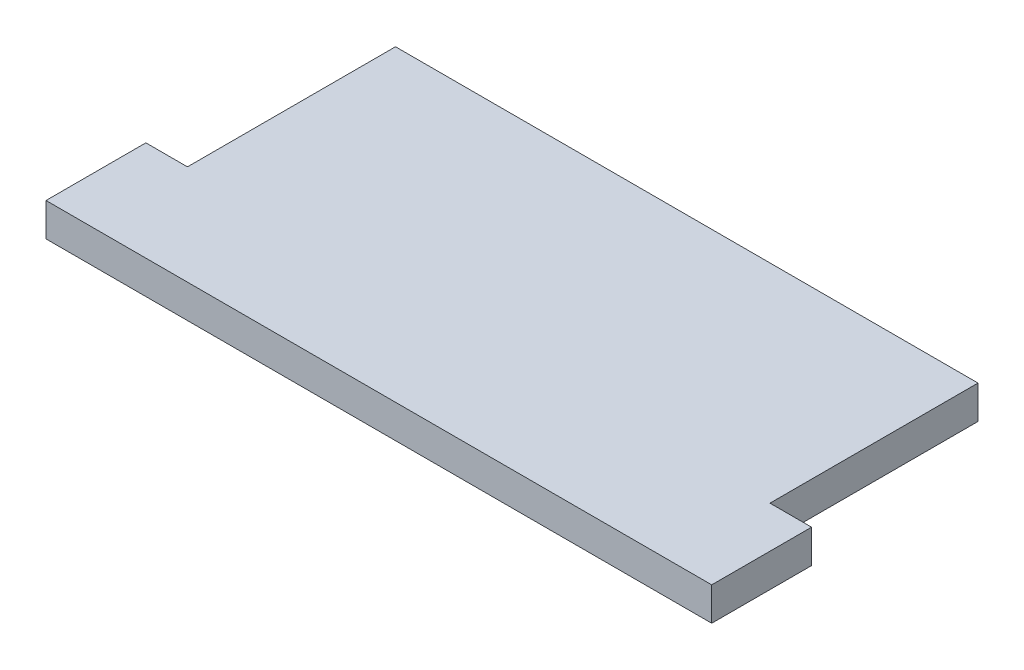
SolidWorks part; units mm, degrees
ref_plane "Front Plane" through (0, 0, 0) normal (0, 0, 1) x (1, 0, 0)
ref_plane "Top Plane" through (0, 0, 0) normal (0, 1, 0) x (1, 0, 0)
ref_plane "Right Plane" through (0, 0, 0) normal (1, 0, 0) x (0, 0, -1)
sketch "Sketch2" plane through (0, 0, 0) normal (0, 1, 0) x (1, 0, 0)
  line L0 (0, 0) -> (40, 0)
  line L1 (40, 0) -> (40, 6)
  line L2 (40, 6) -> (37.5, 6)
  line L3 (37.5, 6) -> (37.5, 18.5)
  line L4 (37.5, 18.5) -> (2.5, 18.5)
  line L5 (2.5, 18.5) -> (2.5, 6)
  line L6 (2.5, 6) -> (0, 6)
  line L7 (0, 6) -> (0, 0)
  dimension "D1" = 6
  dimension "D2" = 40
  dimension "D3" = 6
  dimension "D4" = 12.5
  dimension "D5" = 2.5
  dimension "D6" = 2.5
  dimension "D7" = 12.5
extrude "Boss-Extrude2" add sketch "Sketch2" along normal blind 2
